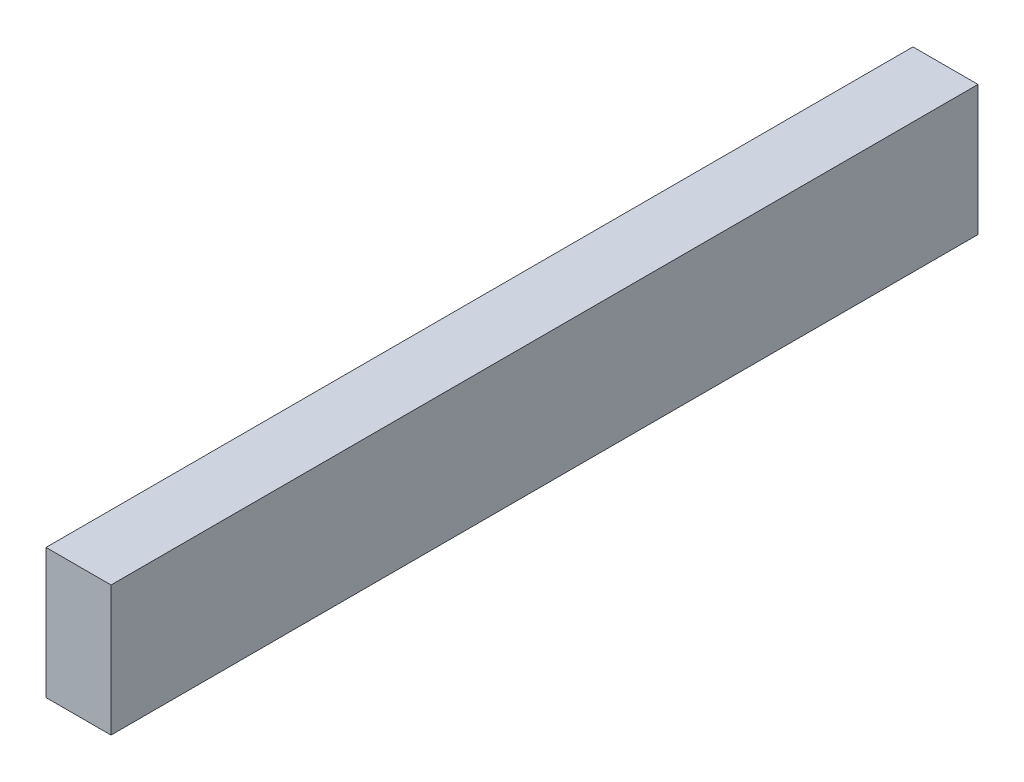
SolidWorks part; units mm, degrees
ref_plane "前基準面" through (0, 0, 0) normal (0, 0, 1) x (1, 0, 0)
ref_plane "上基準面" through (0, 0, 0) normal (0, 1, 0) x (1, 0, 0)
ref_plane "右基準面" through (0, 0, 0) normal (1, 0, 0) x (0, 0, -1)
sketch "草圖1" plane through (0, 0, 0) normal (0, 0, 1) x (1, 0, 0)
  line L1 (15, 15) -> (-15, 15)
  line L2 (15, 15) -> (15, -15)
  line L3 (15, -15) -> (-15, -15)
  line L4 (-15, 15) -> (-15, -15)
  line L5 (0, -15) -> (0, 15) construction
  line L6 (15, 0) -> (-15, 0) construction
  point P0 (0, 0)
  dimension "D1" = 30
  dimension "D2" = 30
extrude "填料-伸長1" add sketch "草圖1" against normal blind 400
mirror "鏡射1" about plane through (15, 15, -400) normal (0, 1, 0) of "填料-伸長1"
